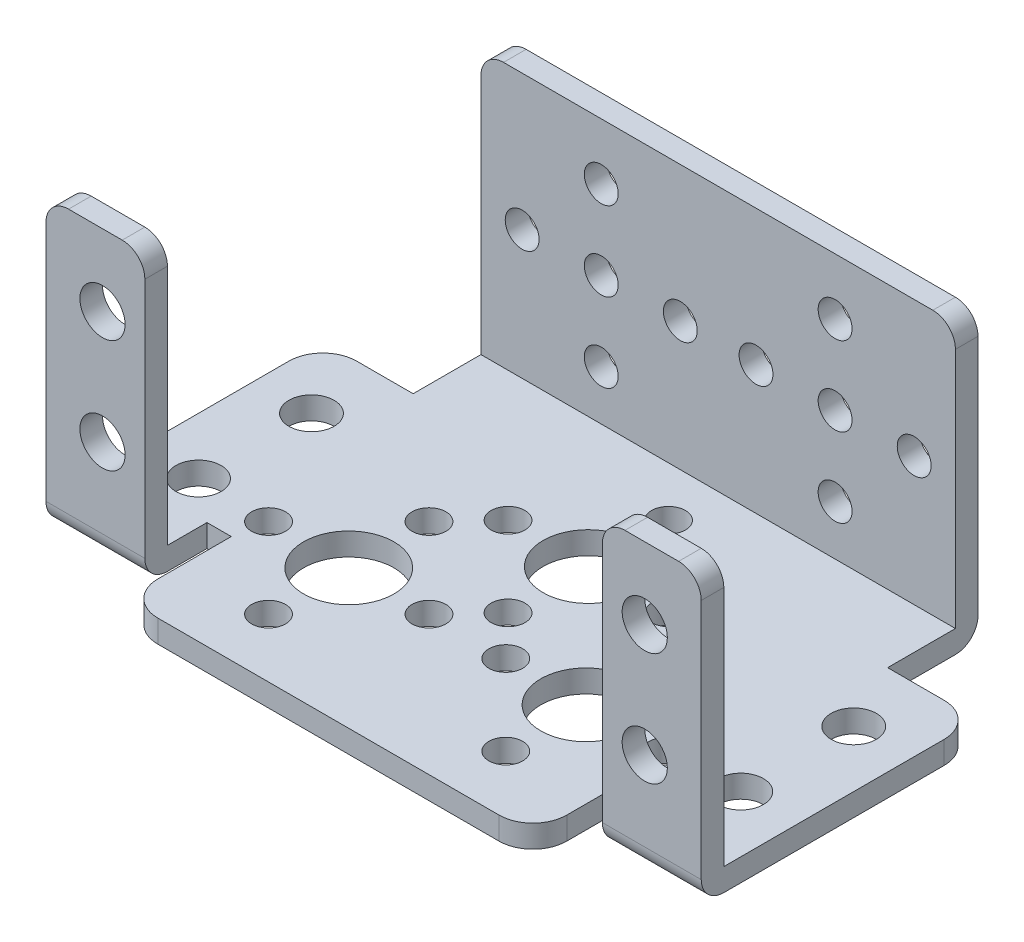
SolidWorks part; units mm, degrees
ref_plane "Front Plane" through (0, 0, 0) normal (0, 0, 1) x (1, 0, 0)
ref_plane "Top Plane" through (0, 0, 0) normal (0, 1, 0) x (1, 0, 0)
ref_plane "Right Plane" through (0, 0, 0) normal (1, 0, 0) x (0, 0, -1)
sketch "Sketch1" plane through (0, 0, 0) normal (0, 1, 0) x (1, 0, 0)
  line L0 (0, 4) -> (0, 25.5)
  line L1 (8, 36.5) -> (50, 36.5)
  line L2 (58, 25.5) -> (58, 4)
  line L3 (44.1, 0) -> (13.9, 0)
  line L5 (8, 36.5) -> (8, 28.5)
  line L6 (8, 28.5) -> (3, 28.5)
  line L7 (50, 36.5) -> (50, 28.5)
  line L8 (50, 28.5) -> (55, 28.5)
  line L11 (10.9, 3) -> (10.9, 9.5)
  line L12 (10.9, 9.5) -> (8.75, 9.5)
  line L13 (8.75, 9.5) -> (8.75, 4)
  line L14 (29, 36.5) -> (29, 0) construction
  line L15 (47.1, 9.5) -> (49.25, 9.5)
  line L16 (47.1, 3) -> (47.1, 9.5)
  line L18 (49.25, 9.5) -> (49.25, 4)
  line L20 (8, 36.5) -> (8, 4) construction
  line L21 (0, 4) -> (58, 4) construction
  line L22 (0, 4) -> (8.75, 4)
  line L23 (49.25, 4) -> (58, 4)
  line L24 (58, 18.25) -> (0, 18.25) construction
  line L25 (29, 36.5) -> (29, 22.5) construction
  line L26 (29, 0) -> (29, 12.3) construction
  line L27 (58, 12.3) -> (39.5, 12.3) construction
  line L28 (18.5, 36.5) -> (18.5, 0) construction
  line L29 (39.5, 36.5) -> (39.5, 0) construction
  line L30 (29, 26.5) -> (29, 29.6) construction
  line L31 (18.5, 16.3) -> (18.5, 19.4) construction
  line L32 (39.5, 16.3) -> (39.5, 19.4) construction
  line L33 (29, 36.5) -> (29, 23) construction
  line L34 (29, 27) -> (29, 30.1) construction
  line L35 (55, 28.5) -> (53, 28.5) construction
  line L36 (53, 28.5) -> (53, 22.5) construction
  line L37 (53, 20.5) -> (53, 12.5) construction
  arc A0 (55, 28.5) -> (58, 25.5) centre (55, 25.5) cw
  arc A1 (3, 28.5) -> (0, 25.5) centre (3, 25.5) ccw
  arc A2 (47.1, 3) -> (44.1, 0) centre (44.1, 3) cw
  arc A3 (13.9, 0) -> (10.9, 3) centre (13.9, 3) cw
  circle A5 centre (39.5, 12.3) radius 4
  circle A6 centre (18.5, 12.3) radius 4
  circle A8 centre (18.5, 19.4) radius 1.5
  circle A9 centre (39.5, 19.4) radius 1.5
  circle A10 centre (46.6, 12.3) radius 1.5
  circle A11 centre (39.5, 5.2) radius 1.5
  circle A12 centre (32.4, 12.3) radius 1.5
  circle A13 centre (25.6, 12.3) radius 1.5
  circle A14 centre (18.5, 5.2) radius 1.5
  circle A15 centre (11.4, 12.3) radius 1.5
  circle A16 centre (29, 23) radius 4
  circle A17 centre (29, 30.1) radius 1.5
  circle A18 centre (36.1, 23) radius 1.5
  circle A19 centre (29, 15.9) radius 1.5
  circle A20 centre (21.9, 23) radius 1.5
  circle A21 centre (53, 22.5) radius 2
  circle A22 centre (5, 22.5) radius 2
  circle A23 centre (53, 12.5) radius 2
  circle A24 centre (5, 12.5) radius 2
  point P13 (0, 28.5)
  point P61 (39.5, 12.3)
  point P68 (18.5, 12.3)
  point P75 (29, 22.5)
  point P79 (29, 23)
  dimension "D5" = 3
  dimension "D1" = 3
  dimension "D2" = 18.5
  dimension "D10" = 4
  dimension "D7" = 4
  dimension "D12" = 8.75
  dimension "D3" = 8
  dimension "D4" = 8
  dimension "D6" = 12.3
  dimension "D8" = 2.15
  dimension "D9" = 29
  dimension "D11" = 4
extrude "Boss-Extrude1" add sketch "Sketch1" along normal blind 2
sketch "Sketch2" plane through (0, 2, 0) normal (0, 1, 0) x (1, 0, 0)
  line L0 (8, 36.5) -> (50, 36.5)
  line L1 (50, 36.5) -> (50, 34.5)
  line L2 (50, 28.5) -> (50, 36.5) construction
  line L3 (50, 34.5) -> (8, 34.5)
  line L4 (8, 36.5) -> (8, 28.5) construction
  line L5 (8, 34.5) -> (8, 36.5)
  line L6 (0, 4) -> (8.75, 4)
  line L7 (8.75, 4) -> (8.75, 6)
  line L8 (8.75, 4) -> (8.75, 9.5) construction
  line L9 (8.75, 6) -> (0, 6)
  line L10 (0, 25.5) -> (0, 4) construction
  line L11 (0, 6) -> (0, 4)
  line L12 (49.25, 4) -> (58, 4)
  line L13 (58, 4) -> (58, 6)
  line L14 (58, 4) -> (58, 25.5) construction
  line L15 (58, 6) -> (49.25, 6)
  line L16 (49.25, 9.5) -> (49.25, 4) construction
  line L17 (49.25, 6) -> (49.25, 4)
extrude "Boss-Extrude2" add sketch "Sketch2" along normal blind 23.4
fillet "Fillet1" radius 2 6 edges at (8, 25.4, -35.5) (50, 25.4, -35.5) (49.25, 25.4, -5) (58, 25.4, -5) (0, 25.4, -5) (8.75, 25.4, -5)
fillet "Fillet2" radius 2 3 edges at (29, 0, -36.5) (4.375, 0, -4) (53.625, 0, -4)
sketch "Sketch3" plane through (0, 0, -4) normal (0, 0, 1) x (1, 0, 0)
  line L0 (0, 23.4) -> (58, 23.4) construction
  line L1 (29, 23.4) -> (29, 0) construction
  line L2 (13.9, 0) -> (44.1, 0) construction
  line L3 (0, 23.4) -> (5, 23.4) construction
  line L4 (5, 23.4) -> (5, 2) construction
  line L5 (0, 2) -> (8.75, 2) construction
  line L6 (5, 25.4) -> (5, 19.05) construction
  line L7 (2, 25.4) -> (6.75, 25.4) construction
  line L8 (5, 17.05) -> (5, 9.05) construction
  circle A0 centre (5, 19.05) radius 2
  circle A1 centre (5, 9.05) radius 2
  circle A2 centre (53, 9.05) radius 2
  circle A3 centre (53, 19.05) radius 2
extrude "Cut-Extrude1" cut sketch "Sketch3" against normal up to next
sketch "Sketch4" plane through (0, 0, -36.5) normal (0, 0, -1) x (-1, 0, 0)
  line L0 (-29, 25.4) -> (-29, 2) construction
  line L1 (-48, 25.4) -> (-10, 25.4) construction
  line L2 (-50, 2) -> (-8, 2) construction
  line L3 (-29, 25.4) -> (-29, 13.4) construction
  line L4 (-18.65, 14.9) -> (-18.65, 20.4) construction
  line L6 (-29, 13.4) -> (-8, 13.4) construction
  line L7 (-8, 23.4) -> (-8, 2) construction
  line L8 (-8, 13.4) -> (-50, 13.4) construction
  line L9 (-50, 23.4) -> (-50, 2) construction
  line L10 (-8, 13.4) -> (-18.65, 13.4) construction
  line L11 (-18.65, 13.4) -> (-18.65, 25.4) construction
  circle A0 centre (-18.65, 13.4) radius 1.5
  circle A1 centre (-18.65, 20.4) radius 1.5
  circle A2 centre (-11.65, 13.4) radius 1.5
  circle A3 centre (-18.65, 6.4) radius 1.5
  circle A4 centre (-25.65, 13.4) radius 1.5
  circle A5 centre (-39.35, 6.4) radius 1.5
  circle A6 centre (-46.35, 13.4) radius 1.5
  circle A7 centre (-39.35, 13.4) radius 1.5
  circle A8 centre (-39.35, 20.4) radius 1.5
  circle A9 centre (-32.35, 13.4) radius 1.5
  point P28 (-18.65, 13.4)
  dimension "D1" = 4
extrude "Cut-Extrude2" cut sketch "Sketch4" against normal up to next
